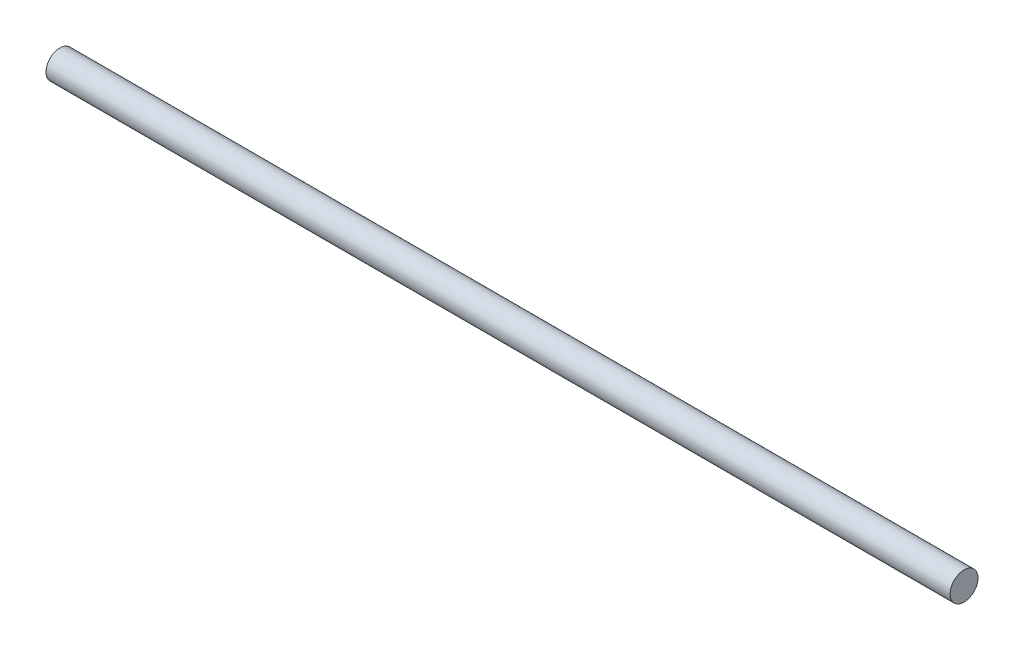
SolidWorks part; units mm, degrees
ref_plane "Front Plane" through (0, 0, 0) normal (0, 0, 1) x (1, 0, 0)
ref_plane "Top Plane" through (0, 0, 0) normal (0, 1, 0) x (1, 0, 0)
ref_plane "Right Plane" through (0, 0, 0) normal (1, 0, 0) x (0, 0, -1)
sketch "Sketch1" plane through (0, 0, 0) normal (1, 0, 0) x (0, 0, -1)
  circle A0 centre (0, 0) radius 12.5
  dimension "D1" = 25
extrude "Boss-Extrude1" add sketch "Sketch1" along normal mid plane 810
